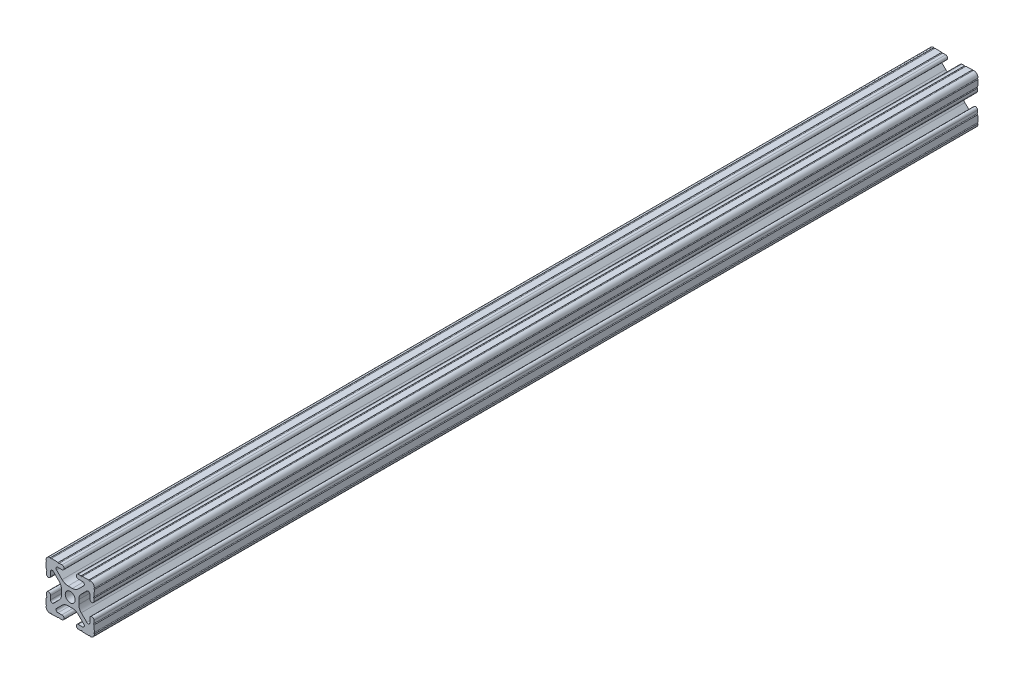
SolidWorks part; units mm, degrees
ref_plane "Front Plane" through (0, 0, 0) normal (0, 0, 1) x (1, 0, 0)
ref_plane "Top Plane" through (0, 0, 0) normal (0, 1, 0) x (1, 0, 0)
ref_plane "Right Plane" through (0, 0, 0) normal (1, 0, 0) x (0, 0, -1)
sketch "Sketch1" plane through (0, 0, 0) normal (0, 0, 1) x (1, 0, 0)
  line L0 (0, 12.7) -> (-12.7814, 12.7) construction
  line L1 (-4.5085, 0) -> (-4.5085, 2.9459)
  line L2 (-6.0437, 12.5461) -> (-10.0976, 12.6876) construction
  line L3 (-11.5616, 12.4229) -> (-4.3159, 12.1699) construction
  line L4 (-6.4364, 10.3486) -> (-6.3592, 12.5571) construction
  line L6 (-2.9459, 4.5085) -> (0, 4.5085)
  line L7 (0, 0) -> (0, 12.7) construction
  line L8 (0, 0) -> (-12.7814, 0) construction
  line L9 (0.7813, 0.7813) -> (-0.7813, -0.7813) construction
  line L10 (-2.9459, 4.5085) -> (-7.1484, 8.711)
  line L11 (-4.5085, 2.9459) -> (-8.711, 7.1484)
  line L13 (0, 0) -> (-12.7814, 12.7814) construction
  line L14 (-10.4131, 12.6987) -> (-4.3048, 12.4853)
  line L15 (-4.3048, 12.4853) -> (-4.382, 10.2769) construction
  line L16 (-4.382, 10.2769) -> (-6.4364, 10.3486)
  line L17 (-12.6987, 10.4131) -> (-12.4853, 4.3048)
  line L18 (-10.2769, 4.382) -> (-10.3486, 6.4364)
  circle A0 centre (0, 0) radius 2.6035
  arc A1 (-4.382, 10.2769) -> (-4.3048, 12.4853) centre (-4.3434, 11.3811) ccw
  arc A2 (-7.1484, 8.711) -> (-6.4364, 10.3486) centre (-6.4698, 9.3896) cw
  arc A3 (-8.711, 7.1484) -> (-10.3486, 6.4364) centre (-9.3896, 6.4698) ccw
  arc A4 (-10.2769, 4.382) -> (-12.4853, 4.3048) centre (-11.3811, 4.3434) cw
  arc A5 (-10.4131, 12.6987) -> (-12.6987, 10.4131) centre (-10.4902, 10.4902) ccw
  arc A6 (-10.4131, 12.6987) -> (-9.7821, 12.6766) centre (-10.0976, 12.6876) ccw
  arc A7 (-6.3592, 12.5571) -> (-5.7282, 12.5351) centre (-6.0437, 12.5461) ccw
  arc A8 (-12.5571, 6.3592) -> (-12.5351, 5.7282) centre (-12.5461, 6.0437) cw
  arc A9 (-12.6987, 10.4131) -> (-12.6766, 9.7821) centre (-12.6876, 10.0976) cw
  dimension "D1" = 5.207
  dimension "D5" = 14.859
  dimension "D9" = 2
  dimension "D2" = 25.4
  dimension "D12" = 0.6314
  dimension "D10" = 2.2098
  dimension "D3" = 9.017
  dimension "D4" = 9.017
  dimension "D6" = 25.4
  dimension "D7" = 6.477
  dimension "D8" = 2.2098
  dimension "D11" = 12.7
sketch "Sketch3" plane through (0, 0, 0) normal (0, 0, 1) x (1, 0, 0)
  line L0 (-2.9459, 4.5085) -> (0, 4.5085) construction
  line L1 (-2.9459, 4.5085) -> (-7.1484, 8.711) construction
  line L2 (-4.382, 10.2769) -> (-6.4364, 10.3486) construction
  line L3 (-10.4131, 12.6987) -> (-4.3048, 12.4853) construction
  line L4 (-4.5085, 0) -> (-4.5085, 2.9459) construction
  line L5 (-4.5085, 2.9459) -> (-8.711, 7.1484) construction
  line L6 (-10.2769, 4.382) -> (-10.3486, 6.4364) construction
  line L7 (-12.6987, 10.4131) -> (-12.4853, 4.3048) construction
  line L8 (-1.1153, 4.5085) -> (1.1153, 4.5085)
  line L9 (-4.2404, 5.803) -> (-7.1484, 8.711)
  line L10 (-4.382, 10.2769) -> (-6.4364, 10.3486)
  line L11 (-9.7821, 12.6766) -> (-6.3592, 12.5571)
  line L12 (-4.5085, -1.1153) -> (-4.5085, 1.1153)
  line L13 (-5.803, 4.2404) -> (-8.711, 7.1484)
  line L14 (-10.2769, 4.382) -> (-10.3486, 6.4364)
  line L15 (-12.6766, 9.7821) -> (-12.5571, 6.3592)
  line L16 (-5.7282, 12.5351) -> (-4.3048, 12.4853)
  line L17 (-12.5351, 5.7282) -> (-12.4853, 4.3048)
  line L18 (0, 0) -> (0, 12.7) construction
  line L19 (0, 0) -> (-12.7814, 0) construction
  line L20 (12.5351, 5.7282) -> (12.4853, 4.3048)
  line L21 (5.7282, 12.5351) -> (4.3048, 12.4853)
  line L22 (12.6766, 9.7821) -> (12.5571, 6.3592)
  line L23 (10.2769, 4.382) -> (10.3486, 6.4364)
  line L24 (5.803, 4.2404) -> (8.711, 7.1484)
  line L25 (4.5085, -1.1153) -> (4.5085, 1.1153)
  line L26 (9.7821, 12.6766) -> (6.3592, 12.5571)
  line L27 (4.382, 10.2769) -> (6.4364, 10.3486)
  line L28 (4.2404, 5.803) -> (7.1484, 8.711)
  line L29 (4.2404, -5.803) -> (7.1484, -8.711)
  line L30 (4.382, -10.2769) -> (6.4364, -10.3486)
  line L31 (9.7821, -12.6766) -> (6.3592, -12.5571)
  line L32 (5.803, -4.2404) -> (8.711, -7.1484)
  line L33 (10.2769, -4.382) -> (10.3486, -6.4364)
  line L34 (12.6766, -9.7821) -> (12.5571, -6.3592)
  line L35 (5.7282, -12.5351) -> (4.3048, -12.4853)
  line L36 (12.5351, -5.7282) -> (12.4853, -4.3048)
  line L37 (-12.5351, -5.7282) -> (-12.4853, -4.3048)
  line L38 (-5.7282, -12.5351) -> (-4.3048, -12.4853)
  line L39 (-12.6766, -9.7821) -> (-12.5571, -6.3592)
  line L40 (-10.2769, -4.382) -> (-10.3486, -6.4364)
  line L41 (-5.803, -4.2404) -> (-8.711, -7.1484)
  line L42 (-9.7821, -12.6766) -> (-6.3592, -12.5571)
  line L43 (-4.382, -10.2769) -> (-6.4364, -10.3486)
  line L44 (-4.2404, -5.803) -> (-7.1484, -8.711)
  line L45 (-1.1153, -4.5085) -> (1.1153, -4.5085)
  arc A0 (-10.4131, 12.6987) -> (-9.7821, 12.6766) centre (-10.0976, 12.6876) ccw construction
  arc A1 (-6.4364, 10.3486) -> (-7.1484, 8.711) centre (-6.4698, 9.3896) ccw construction
  arc A2 (-4.382, 10.2769) -> (-4.3048, 12.4853) centre (-4.3434, 11.3811) ccw construction
  arc A3 (-8.711, 7.1484) -> (-10.3486, 6.4364) centre (-9.3896, 6.4698) ccw construction
  arc A4 (-12.4853, 4.3048) -> (-10.2769, 4.382) centre (-11.3811, 4.3434) ccw construction
  arc A5 (-6.3592, 12.5571) -> (-5.7282, 12.5351) centre (-6.0437, 12.5461) ccw construction
  arc A6 (-10.4131, 12.6987) -> (-12.6987, 10.4131) centre (-10.4902, 10.4902) ccw construction
  arc A7 (-12.6766, 9.7821) -> (-12.6987, 10.4131) centre (-12.6876, 10.0976) ccw construction
  arc A8 (-12.5351, 5.7282) -> (-12.5571, 6.3592) centre (-12.5461, 6.0437) ccw construction
  arc A9 (-10.4131, 12.6987) -> (-9.7821, 12.6766) centre (-10.0976, 12.6876) ccw
  arc A10 (-6.4364, 10.3486) -> (-7.1484, 8.711) centre (-6.4698, 9.3896) ccw
  arc A11 (-4.382, 10.2769) -> (-4.3048, 12.4853) centre (-4.3434, 11.3811) ccw
  arc A12 (-8.711, 7.1484) -> (-10.3486, 6.4364) centre (-9.3896, 6.4698) ccw
  arc A13 (-12.4853, 4.3048) -> (-10.2769, 4.382) centre (-11.3811, 4.3434) ccw
  arc A14 (-6.3592, 12.5571) -> (-5.7282, 12.5351) centre (-6.0437, 12.5461) ccw
  arc A15 (-10.4131, 12.6987) -> (-12.6987, 10.4131) centre (-10.4902, 10.4902) ccw
  arc A16 (-12.6766, 9.7821) -> (-12.6987, 10.4131) centre (-12.6876, 10.0976) ccw
  arc A17 (-12.5351, 5.7282) -> (-12.5571, 6.3592) centre (-12.5461, 6.0437) ccw
  arc A18 (-1.1153, 4.5085) -> (-4.2404, 5.803) centre (-1.1153, 8.9281) cw
  arc A19 (4.5085, 1.1153) -> (5.803, 4.2404) centre (8.9281, 1.1153) cw
  arc A20 (1.1153, 4.5085) -> (4.2404, 5.803) centre (1.1153, 8.9281) ccw
  arc A21 (-4.5085, 1.1153) -> (-5.803, 4.2404) centre (-8.9281, 1.1153) ccw
  arc A22 (12.5351, 5.7282) -> (12.5571, 6.3592) centre (12.5461, 6.0437) cw
  arc A23 (12.6766, 9.7821) -> (12.6987, 10.4131) centre (12.6876, 10.0976) cw
  arc A24 (10.4131, 12.6987) -> (12.6987, 10.4131) centre (10.4902, 10.4902) cw
  arc A25 (6.3592, 12.5571) -> (5.7282, 12.5351) centre (6.0437, 12.5461) cw
  arc A26 (12.4853, 4.3048) -> (10.2769, 4.382) centre (11.3811, 4.3434) cw
  arc A27 (8.711, 7.1484) -> (10.3486, 6.4364) centre (9.3896, 6.4698) cw
  arc A28 (4.382, 10.2769) -> (4.3048, 12.4853) centre (4.3434, 11.3811) cw
  arc A29 (6.4364, 10.3486) -> (7.1484, 8.711) centre (6.4698, 9.3896) cw
  arc A30 (10.4131, 12.6987) -> (9.7821, 12.6766) centre (10.0976, 12.6876) cw
  arc A31 (10.4131, -12.6987) -> (9.7821, -12.6766) centre (10.0976, -12.6876) ccw
  arc A32 (6.4364, -10.3486) -> (7.1484, -8.711) centre (6.4698, -9.3896) ccw
  arc A33 (4.382, -10.2769) -> (4.3048, -12.4853) centre (4.3434, -11.3811) ccw
  arc A34 (8.711, -7.1484) -> (10.3486, -6.4364) centre (9.3896, -6.4698) ccw
  arc A35 (12.4853, -4.3048) -> (10.2769, -4.382) centre (11.3811, -4.3434) ccw
  arc A36 (6.3592, -12.5571) -> (5.7282, -12.5351) centre (6.0437, -12.5461) ccw
  arc A37 (10.4131, -12.6987) -> (12.6987, -10.4131) centre (10.4902, -10.4902) ccw
  arc A38 (12.6766, -9.7821) -> (12.6987, -10.4131) centre (12.6876, -10.0976) ccw
  arc A39 (12.5351, -5.7282) -> (12.5571, -6.3592) centre (12.5461, -6.0437) ccw
  arc A40 (-4.5085, -1.1153) -> (-5.803, -4.2404) centre (-8.9281, -1.1153) cw
  arc A41 (1.1153, -4.5085) -> (4.2404, -5.803) centre (1.1153, -8.9281) cw
  arc A42 (4.5085, -1.1153) -> (5.803, -4.2404) centre (8.9281, -1.1153) ccw
  arc A43 (-1.1153, -4.5085) -> (-4.2404, -5.803) centre (-1.1153, -8.9281) ccw
  arc A44 (-12.5351, -5.7282) -> (-12.5571, -6.3592) centre (-12.5461, -6.0437) cw
  arc A45 (-12.6766, -9.7821) -> (-12.6987, -10.4131) centre (-12.6876, -10.0976) cw
  arc A46 (-10.4131, -12.6987) -> (-12.6987, -10.4131) centre (-10.4902, -10.4902) cw
  arc A47 (-6.3592, -12.5571) -> (-5.7282, -12.5351) centre (-6.0437, -12.5461) cw
  arc A48 (-12.4853, -4.3048) -> (-10.2769, -4.382) centre (-11.3811, -4.3434) cw
  arc A49 (-8.711, -7.1484) -> (-10.3486, -6.4364) centre (-9.3896, -6.4698) cw
  arc A50 (-4.382, -10.2769) -> (-4.3048, -12.4853) centre (-4.3434, -11.3811) cw
  arc A51 (-6.4364, -10.3486) -> (-7.1484, -8.711) centre (-6.4698, -9.3896) cw
  arc A52 (-10.4131, -12.6987) -> (-9.7821, -12.6766) centre (-10.0976, -12.6876) cw
  circle A53 centre (0, 0) radius 2.6035 construction
  circle A54 centre (0, 0) radius 2.6035
  point P135 (4.5085, 0)
  dimension "D2" = 4.4196
extrude "Extrude1" add sketch "Sketch3" along normal mid plane 464
equation "\"D10@Sketch1\" = \"D8@Sketch1\""
equation "\"D11@Sketch1\" = \"D6@Sketch1\"/2"
equation "\"D12@Sketch1\" = \"D8@Sketch1\"/3.5"
equation "\"D2@Sketch3\" = \"D8@Sketch1\"*2"
